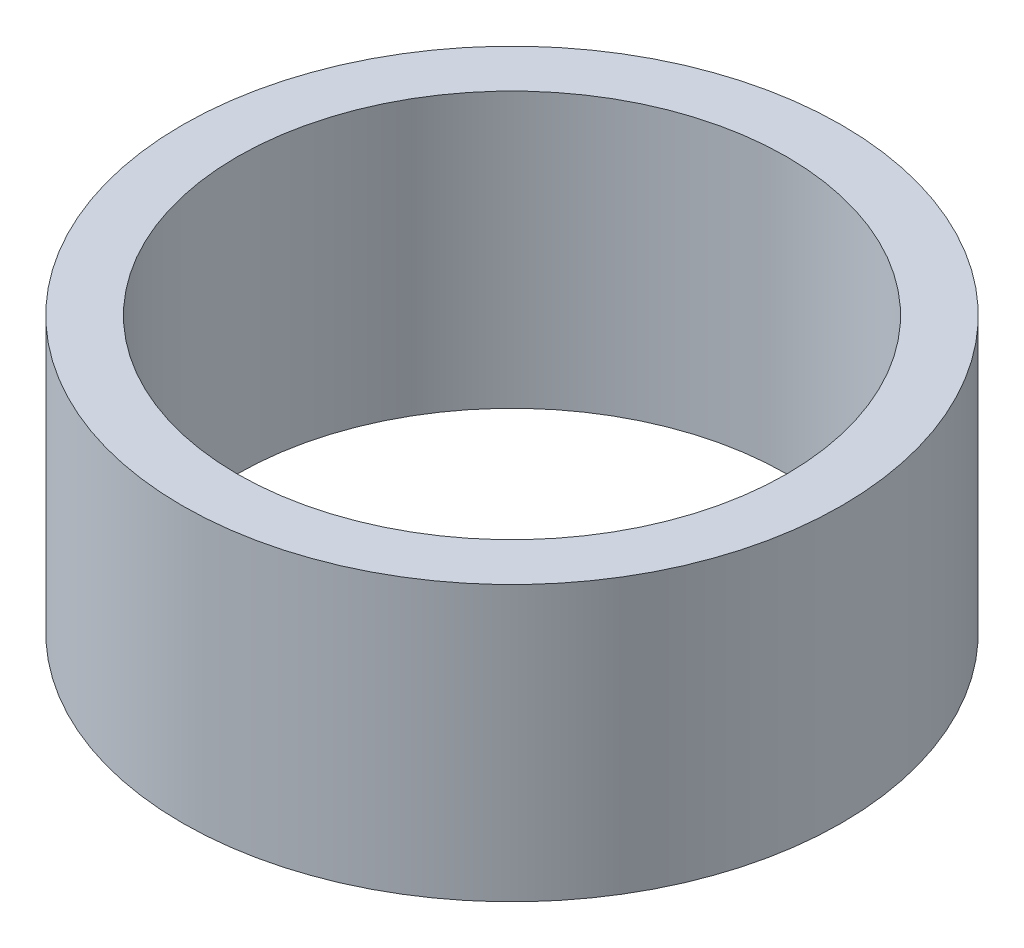
SolidWorks part; units mm, degrees
ref_plane "Спереди" through (0, 0, 0) normal (0, 0, 1) x (1, 0, 0)
ref_plane "Сверху" through (0, 0, 0) normal (0, 1, 0) x (1, 0, 0)
ref_plane "Справа" through (0, 0, 0) normal (1, 0, 0) x (0, 0, -1)
sketch "Эскиз1" plane through (0, 0, 0) normal (0, 1, 0) x (1, 0, 0)
  circle A0 centre (-2.1296, 0.8314) radius 5
  circle A1 centre (-2.1296, 0.8314) radius 6
  dimension "D1" = 10
  dimension "D2" = 12
extrude "Бобышка-Вытянуть1" add sketch "Эскиз1" along normal blind 5
